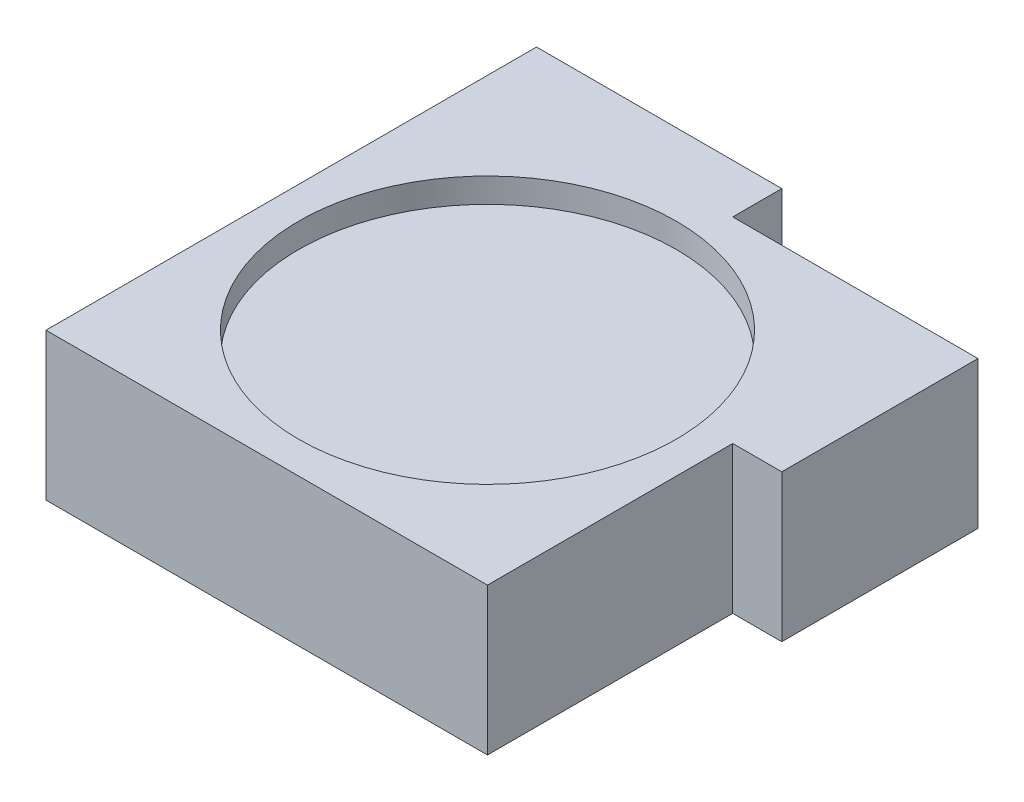
SolidWorks part; units mm, degrees
ref_plane "Front Plane" through (0, 0, 0) normal (0, 0, 1) x (1, 0, 0)
ref_plane "Top Plane" through (0, 0, 0) normal (0, 1, 0) x (1, 0, 0)
ref_plane "Right Plane" through (0, 0, 0) normal (1, 0, 0) x (0, 0, -1)
sketch "Sketch1" plane through (0, 0, 0) normal (0, 1, 0) x (1, 0, 0)
  line L0 (50, 100) -> (50, 90)
  line L5 (0, 0) -> (90, 0)
  line L6 (0, 0) -> (0, 100)
  line L7 (0, 100) -> (50, 100)
  line L8 (90, 0) -> (90, 50)
  line L9 (50, 90) -> (100, 90)
  line L10 (100, 90) -> (100, 50)
  line L11 (100, 50) -> (90, 50)
extrude "Boss-Extrude2" add sketch "Sketch1" along normal blind 30 contours L8 L11 L10 L9 L0 L7 L6 L5
sketch "Sketch2" plane through (0, 30, 0) normal (0, 1, 0) x (1, 0, 0)
  circle A0 centre (45, 45) radius 38.5
  point P2 (0, 0)
extrude "Cut-Extrude2" cut sketch "Sketch2" against normal blind 5
